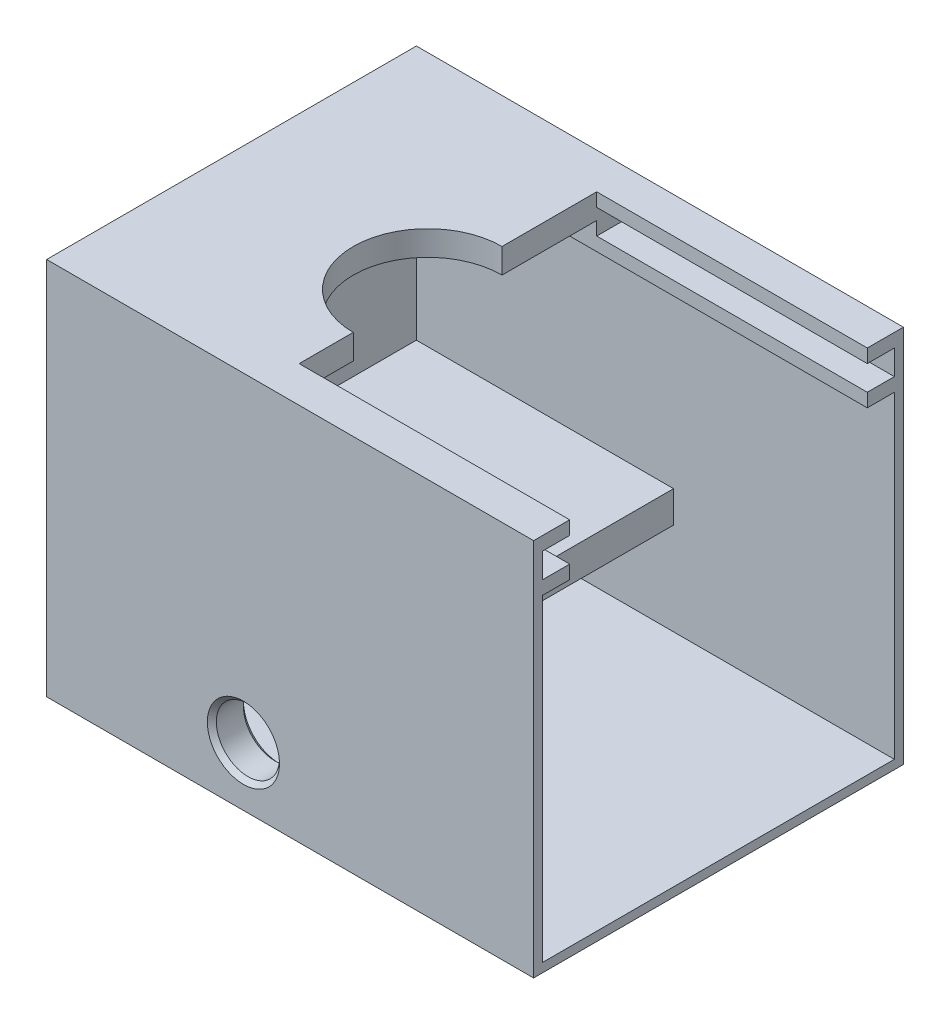
SolidWorks part; units mm, degrees
ref_plane "Front Plane" through (0, 0, 0) normal (0, 0, 1) x (1, 0, 0)
ref_plane "Top Plane" through (0, 0, 0) normal (0, 1, 0) x (1, 0, 0)
ref_plane "Right Plane" through (0, 0, 0) normal (1, 0, 0) x (0, 0, -1)
sketch "Sketch2" plane through (0, 0, 0) normal (0, 1, 0) x (1, 0, 0)
  line L1 (84.1818, -57.3934) -> (-28.8182, -57.3934)
  line L2 (84.1818, -57.3934) -> (84.1818, 19.6066)
  line L3 (84.1818, 19.6066) -> (-28.8182, 19.6066)
  line L4 (-28.8182, -57.3934) -> (-28.8182, 19.6066)
  dimension "D1" = 113
  dimension "D2" = 77
extrude "Boss-Extrude1" add sketch "Sketch2" along normal blind 80
sketch "Sketch3" plane through (84.1818, 0, 0) normal (1, 0, 0) x (0, 0, -1)
  line L0 (-57.3934, 80) -> (-57.3934, 0) construction
  line L1 (-55.3934, 80) -> (17.6066, 80)
  line L2 (-55.3934, 80) -> (-55.3934, 2)
  line L3 (-55.3934, 2) -> (17.6066, 2)
  line L4 (17.6066, 80) -> (17.6066, 2)
  line L5 (19.6066, 80) -> (19.6066, 0) construction
  line L6 (-57.3934, 0) -> (19.6066, 0) construction
  line L7 (-57.3934, 80) -> (19.6066, 80) construction
  dimension "D1" = 2
  dimension "D2" = 2
  dimension "D3" = 2
  dimension "D4" = 0
extrude "Cut-Extrude1" cut sketch "Sketch3" against normal blind 111
sketch "Sketch4" plane through (0, 0, 57.3934) normal (0, 0, 1) x (1, 0, 0)
  line L0 (-28.8182, 0) -> (84.1818, 0) construction
  line L1 (-28.8182, 80) -> (-28.8182, 0) construction
  circle A0 centre (19.8218, 13) radius 7
  dimension "D1" = 14
  dimension "D2" = 13
  dimension "D3" = 48.64
extrude "Cut-Extrude2" cut sketch "Sketch4" against normal blind 43
chamfer "Chamfer1" distance 1 angle 45 1 edges at (26.8218, 13, 57.3934)
sketch "Sketch5" plane through (0, 0, 55.3934) normal (0, 0, -1) x (-1, 0, 0)
  circle A0 centre (-19.8218, 13) radius 9
  dimension "D1" = 18
extrude "Boss-Extrude2" add sketch "Sketch5" along normal blind 6
hole_wizard "CSK for M12 SFHCS1" positions "Sketch6" profile "Sketch7" countersink size "M12" standard "ANSI Metric"
sketch "Sketch6" plane through (0, 0, 49.3934) normal (0, 0, -1) x (-1, 0, 0)
  point P0 (-19.8218, 13)
sketch "Sketch7" plane through (19.8218, 13, 49.3934) normal (1, 0, 0) x (0, 1, 0)
  line L0 (0, 0) -> (0, 12.206)
  line L1 (0, 12.206) -> (7, 8)
  line L2 (7, 8) -> (7, 1)
  line L3 (7, 1) -> (8, 0)
  line L5 (8, 0) -> (0, 0)
  line L6 (-7, 1) -> (-8, 0) construction
  line L10 (0, 12.206) -> (-7, 8) construction
  line L11 (0, -6.35) -> (0, 107.95) construction
  dimension "Hole Dia." = 14
  dimension "Hole Depth" = 8
  dimension "Near C'Sink Dia." = 16
  dimension "Near C'Sink Angle" = 90
  dimension "Drill Angle" = 118
ref_plane "Plane3" through (25.2118, 0, 0) normal (1, 0, 0) x (0, 0, -1)
sketch "Sketch8" plane through (25.2118, 0, 0) normal (1, 0, 0) x (0, 0, -1)
  line L0 (-35.8934, 29.5) -> (-5.8934, 29.5)
  line L1 (-31.4934, 25.1) -> (-33.4934, 25.1)
  line L4 (-35.8934, 22.5) -> (-31.4934, 22.5)
  line L5 (-31.4934, 22.5) -> (-31.4934, 25.1)
  line L6 (-33.4934, 25.1) -> (-33.4934, 27.1)
  line L7 (-5.8934, 22.5) -> (-10.2934, 22.5)
  line L8 (-10.2934, 22.5) -> (-10.2934, 25.1)
  line L9 (-10.2934, 25.1) -> (-8.2934, 25.1)
  line L10 (-8.2934, 25.1) -> (-8.2934, 27.1)
  line L11 (-33.4934, 27.1) -> (-8.2934, 27.1)
  line L12 (-55.3934, 80) -> (-55.3934, 2) construction
  line L13 (-35.8934, 22.5) -> (-55.3934, 22.5)
  line L14 (-55.3934, 2) -> (17.6066, 2) construction
  line L15 (-55.3934, 22.5) -> (-55.3934, 29.5)
  line L16 (-55.3934, 29.5) -> (-35.8934, 29.5)
  line L17 (17.6066, 2) -> (17.6066, 80) construction
  line L18 (-5.8934, 29.5) -> (17.6066, 29.5)
  line L20 (-5.8934, 22.5) -> (17.6066, 22.5)
  line L21 (17.6066, 29.5) -> (17.6066, 22.5)
  dimension "D1" = 30
  dimension "D2" = 7
  dimension "D3" = 7
  dimension "D4" = 4.4
  dimension "D5" = 2.6
  dimension "D6" = 2
  dimension "D7" = 2
  dimension "D8" = 4.4
  dimension "D9" = 2.6
  dimension "D10" = 2
  dimension "D11" = 2
  dimension "D13" = 20.5
sketch "Sketch9" plane through (-28.8182, 0, 0) normal (-1, 0, 0) x (0, 0, 1)
  line L1 (-19.6066, 80) -> (-19.6066, 0) construction
  line L2 (55.3934, 2) -> (-17.6066, 2) construction
  circle A0 centre (18.8934, 52) radius 2.5
  dimension "D1" = 5
  dimension "D2" = 50
  dimension "D3" = 38.5
extrude "Boss-Extrude3" add sketch "Sketch8" against normal blind 51.03 and the other way blind 10
sketch "Sketch11" plane through (0, 29.5, 0) normal (0, 1, 0) x (1, 0, 0)
  line L3 (35.2118, -30.8934) -> (25.2118, -30.8934)
  line L4 (35.2118, 17.6066) -> (35.2118, -55.3934) construction
  line L5 (35.2118, -55.3934) -> (-25.8182, -55.3934) construction
  line L6 (35.2118, -10.8934) -> (25.2118, -10.8934)
  arc A1 (25.2118, -30.8934) -> (25.2118, -10.8934) centre (25.2118, -20.8934) cw
  dimension "D1" = 10
  dimension "D2" = 24.5
  dimension "D3" = 10
  dimension "D4" = 20
extrude "Cut-Extrude4" cut sketch "Sketch9" against normal blind 18.03
sketch "Sketch15" plane through (-28.8182, 0, 0) normal (-1, 0, 0) x (0, 0, 1)
  line L0 (18.8902, 55.5) -> (16.9398, 65.3579)
  line L1 (16.8347, 54.8305) -> (7.7071, 59.5576)
  arc A0 (18.8902, 55.5) -> (16.8347, 54.8305) centre (18.8934, 52) ccw
  arc A1 (16.9398, 65.3579) -> (7.7071, 59.5576) centre (18.8934, 52) ccw
  dimension "D1" = 7
  dimension "D2" = 27
  dimension "D3" = 51.429
  dimension "D4" = 10.049
  dimension "D5" = 10.279
extrude "Cut-Extrude5" cut sketch "Sketch15" along normal blind 23.03 and the other way blind 30
ref_plane "Plane4" through (0, 52, 0) normal (0, 1, 0) x (1, 0, 0)
sketch "Sketch18" plane through (0, 52, 0) normal (0, 1, 0) x (1, 0, 0)
  line L1 (-26.8182, -18.8934) -> (-12.543, -18.8934)
pattern_circular "CirPattern1" count 6 over 360 about axis through (0, 52, 18.8934) along (1, 0, 0) of "Cut-Extrude5"
sketch "Sketch23" plane through (0, 80, 0) normal (0, 1, 0) x (1, 0, 0)
  line L1 (84.1818, -57.3934) -> (-28.8182, -57.3934)
  line L2 (84.1818, -57.3934) -> (84.1818, 19.6066)
  line L3 (84.1818, 19.6066) -> (-28.8182, 19.6066)
  line L4 (-28.8182, -57.3934) -> (-28.8182, 19.6066)
extrude "Boss-Extrude5" add sketch "Sketch23" along normal blind 4 and the other way blind 7.5
sketch "Sketch24" plane through (0, 84, 0) normal (0, 1, 0) x (1, 0, 0)
  line L0 (84.1818, -57.3934) -> (84.1818, 19.6066) construction
  line L2 (84.1818, -37.3934) -> (84.1818, -4.3934)
  line L4 (24.1818, -37.3934) -> (24.1818, -4.3934)
  arc A0 (24.1818, -37.3934) -> (24.1818, -4.3934) centre (24.1818, -20.8934) cw
  dimension "D2" = 60
  dimension "D3" = 33
extrude "Cut-Extrude6" cut sketch "Sketch24" against normal blind 10 contours A0 L4
sketch "Sketch27" plane through (0, 84, 0) normal (0, 1, 0) x (1, 0, 0)
  line L0 (84.1818, -57.3934) -> (84.1818, 19.6066) construction
  line L1 (84.1818, -49.3934) -> (24.1818, -49.3934)
  line L2 (84.1818, -49.3934) -> (84.1818, 16.6066)
  line L3 (84.1818, 16.6066) -> (24.1818, 16.6066)
  line L4 (24.1818, -49.3934) -> (24.1818, 16.6066)
  line L5 (-28.8182, -57.3934) -> (84.1818, -57.3934) construction
  line L6 (84.1818, 19.6066) -> (-28.8182, 19.6066) construction
  dimension "D1" = 60
  dimension "D2" = 8
  dimension "D3" = 3
extrude "Cut-Extrude7" cut sketch "Sketch27" against normal blind 14
sketch "Sketch28" plane through (84.1818, 0, 0) normal (1, 0, 0) x (0, 0, -1)
  line L0 (-49.3934, 72.5) -> (-49.3934, 84) construction
  line L1 (-49.3934, 80.8) -> (-51.1934, 80.8)
  line L2 (-49.3934, 80.8) -> (-49.3934, 83)
  line L3 (-49.3934, 83) -> (-51.1934, 83)
  line L4 (-51.1934, 80.8) -> (-51.1934, 83)
  line L5 (-57.3934, 84) -> (-49.3934, 84) construction
  line L7 (16.6066, 84) -> (16.6066, 72.5) construction
  line L8 (16.6066, 83) -> (18.4066, 83)
  line L9 (16.6066, 83) -> (16.6066, 80.8)
  line L10 (16.6066, 80.8) -> (18.4066, 80.8)
  line L11 (18.4066, 83) -> (18.4066, 80.8)
  line L12 (16.6066, 84) -> (19.6066, 84) construction
  dimension "D1" = 1.8
  dimension "D2" = 2.2
  dimension "D3" = 1
  dimension "D4" = 1.8
  dimension "D5" = 2.2
  dimension "D6" = 1
extrude "Cut-Extrude9" cut sketch "Sketch11" against normal blind 10 and the other way through all
sketch "Sketch29" plane through (24.1818, 0, 0) normal (1, 0, 0) x (0, 0, -1)
  line L0 (16.6066, 72.5) -> (16.6066, 84) construction
  line L1 (-49.3934, 72.5) -> (16.6066, 72.5)
  line L2 (-49.3934, 72.5) -> (-49.3934, 78.5)
  line L3 (-49.3934, 78.5) -> (16.6066, 78.5)
  line L4 (16.6066, 72.5) -> (16.6066, 78.5)
  dimension "D1" = 6
extrude "Cut-Extrude10" cut sketch "Sketch29" against normal blind 51
sketch "Sketch30" plane through (84.1818, 0, 0) normal (1, 0, 0) x (0, 0, -1)
  line L7 (-49.3934, 81) -> (-49.3934, 75.5)
  line L8 (-49.3934, 72.5) -> (-49.3934, 84) construction
  line L9 (-49.3934, 75.5) -> (-55.3934, 75.5)
  line L10 (-55.3934, 75.5) -> (-55.3934, 81)
  line L11 (-55.3934, 81) -> (-49.3934, 81)
  line L12 (-57.3934, 84) -> (-49.3934, 84) construction
  dimension "D1" = 5.5
  dimension "D2" = 6
  dimension "D3" = 3
extrude "Cut-Extrude11" cut sketch "Sketch30" against normal blind 60
sketch "Sketch36" plane through (0, 0, -19.6066) normal (0, 0, -1) x (-1, 0, 0)
  line L1 (-84.1818, 0) -> (28.8182, 0)
  line L2 (-84.1818, 0) -> (-84.1818, 84)
  line L3 (-84.1818, 84) -> (28.8182, 84)
  line L4 (28.8182, 0) -> (28.8182, 84)
extrude "Boss-Extrude9" add sketch "Sketch36" along normal blind 5
sketch "Sketch40" plane through (-26.8182, 0, 0) normal (1, 0, 0) x (0, 0, -1)
  line L1 (-8.1947, 27.1367) -> (-33.6268, 27.1367)
  line L2 (-8.1947, 27.1367) -> (-8.1947, 25.088)
  line L3 (-8.1947, 25.088) -> (-33.6268, 25.088)
  line L4 (-33.6268, 27.1367) -> (-33.6268, 25.088)
extrude "Boss-Extrude10" add sketch "Sketch40" along normal blind 35.8
sketch "Sketch42" plane through (84.1818, 0, 0) normal (1, 0, 0) x (0, 0, -1)
  line L0 (16.6066, 84) -> (16.6066, 72.5) construction
  line L1 (16.6066, 81) -> (22.6066, 81)
  line L2 (16.6066, 81) -> (16.6066, 75.5)
  line L3 (16.6066, 75.5) -> (22.6066, 75.5)
  line L4 (22.6066, 81) -> (22.6066, 75.5)
  line L5 (16.6066, 84) -> (24.6066, 84) construction
  dimension "D1" = 5.5
  dimension "D2" = 3
  dimension "D3" = 6
extrude "Cut-Extrude13" cut sketch "Sketch42" against normal blind 60
sketch "Sketch46" plane through (0, 29.5, 0) normal (0, 1, 0) x (1, 0, 0)
  line L0 (35.2118, -55.3934) -> (-25.8182, -55.3934) construction
  line L1 (-25.8182, 17.6066) -> (-26.8182, 17.6066)
  line L2 (-25.8182, 17.6066) -> (-25.8182, -55.3934)
  line L3 (-25.8182, -55.3934) -> (-26.8182, -55.3934)
  line L4 (-26.8182, 17.6066) -> (-26.8182, -55.3934)
extrude "Boss-Extrude11" add sketch "Sketch46" against normal up to surface (7 mm away) up to face at (4.6968, 22.5, 43.4434)
sketch "Sketch47" plane through (0, 0, -17.6066) normal (0, 0, 1) x (1, 0, 0)
  line L0 (-26.8182, 22.5) -> (-26.8182, 2)
  line L1 (-26.8182, 72.5) -> (84.1818, 72.5)
  line L2 (-26.8182, 72.5) -> (-26.8182, 29.5)
  line L3 (-26.8182, 2) -> (84.1818, 2)
  line L4 (84.1818, 72.5) -> (84.1818, 2)
  line L5 (35.2118, 22.5) -> (-26.8182, 22.5)
  line L6 (35.2118, 22.5) -> (35.2118, 29.5)
  line L7 (35.2118, 29.5) -> (-26.8182, 29.5)
extrude "Cut-Extrude14" cut sketch "Sketch47" against normal blind 5
sketch "Sketch48" plane through (0, 0, 55.3934) normal (0, 0, -1) x (-1, 0, 0)
  line L0 (26.8182, 2) -> (-84.1818, 2) construction
  line L1 (-35.2118, 22.5) -> (26.8182, 22.5) construction
  line L2 (5.6327, 2) -> (-28.8218, 2)
  line L3 (-28.8218, 22.5) -> (5.6327, 22.5)
  line L4 (-10.8218, 13) -> (5.6327, 2)
  line L5 (-10.8218, 13) -> (5.6327, 22.5)
  line L6 (-28.8218, 2) -> (-28.8218, 22.5)
  circle A0 centre (-19.8218, 13) radius 9 construction
  circle A1 centre (-19.8218, 13) radius 9
  circle M6 centre (-19.8218, 13) radius 9
  line M11 (-84.1818, 2) -> (26.8182, 2)
  line M13 (26.8182, 22.5) -> (-35.2118, 22.5)
  dimension "D1" = 30
extrude "Boss-Extrude12" add sketch "Sketch48" along normal up to surface (6 mm away) contours L6 L4 M11 M6 | L6 L5 M6 M13 up to face at (19.8218, 21, 49.3934)
ref_plane "Plane5" through (-23.8182, 0, 0) normal (-1, 0, 0) x (0, 0, 1)
sketch "Sketch49" plane through (-23.8182, 0, 0) normal (-1, 0, 0) x (0, 0, 1)
  line L0 (22.374, 52.3677) -> (31.0316, 57.9088) construction
  line L1 (31.4385, 47.0129) -> (21.9261, 50.2527) construction
  line L2 (20.9521, 49.1695) -> (30.0797, 44.4424) construction
  line L3 (20.847, 38.6421) -> (18.8966, 48.5) construction
  line L4 (57.3934, 84) -> (-24.6066, 84)
  line L5 (-24.6066, 84) -> (-24.6066, 0)
  line L6 (-24.6066, 0) -> (57.3934, 0)
  line L7 (57.3934, 0) -> (57.3934, 84)
  line L8 (57.3934, 84) -> (-24.6066, 84)
  line L9 (-24.6066, 84) -> (-24.6066, 0)
  line L10 (-24.6066, 0) -> (57.3934, 0)
  line L11 (57.3934, 0) -> (57.3934, 84)
  line L12 (17.4715, 48.8019) -> (17.9415, 38.5336) construction
  line L13 (8.3019, 43.6292) -> (15.8639, 50.2473) construction
  line L14 (15.4128, 51.6323) -> (6.7552, 46.0912) construction
  line L15 (6.3483, 56.9871) -> (15.8607, 53.7473) construction
  line L16 (16.8347, 54.8305) -> (7.7071, 59.5576) construction
  line L17 (16.9398, 65.3579) -> (18.8902, 55.5) construction
  line L18 (20.3153, 55.1981) -> (19.8453, 65.4664) construction
  line L19 (29.4849, 60.3708) -> (21.9229, 53.7527) construction
  line L20 (22.374, 52.3677) -> (31.0316, 57.9088)
  line L21 (31.4385, 47.0129) -> (21.9261, 50.2527)
  line L22 (20.9521, 49.1695) -> (30.0797, 44.4424)
  line L23 (20.847, 38.6421) -> (18.8966, 48.5)
  line L24 (17.4715, 48.8019) -> (17.9415, 38.5336)
  line L25 (8.3019, 43.6292) -> (15.8639, 50.2473)
  line L26 (15.4128, 51.6323) -> (6.7552, 46.0912)
  line L27 (6.3483, 56.9871) -> (15.8607, 53.7473)
  line L28 (16.8347, 54.8305) -> (7.7071, 59.5576)
  line L29 (16.9398, 65.3579) -> (18.8902, 55.5)
  line L30 (20.3153, 55.1981) -> (19.8453, 65.4664)
  line L31 (29.4849, 60.3708) -> (21.9229, 53.7527)
  line L32 (55.3934, 22.5) -> (-22.6066, 22.5) construction
  line L33 (-22.6066, 29.5) -> (55.3934, 29.5) construction
  line L34 (55.3934, 22.5) -> (-22.6066, 22.5)
  line L35 (-22.6066, 29.5) -> (55.3934, 29.5)
  arc A0 (31.4385, 47.0129) -> (31.0316, 57.9088) centre (18.8934, 52) ccw construction
  arc A1 (21.9261, 50.2527) -> (22.374, 52.3677) centre (18.8934, 52) ccw construction
  circle A2 centre (18.8934, 52) radius 2.5 construction
  arc A3 (18.8966, 48.5) -> (20.9521, 49.1695) centre (18.8934, 52) ccw construction
  arc A4 (20.847, 38.6421) -> (30.0797, 44.4424) centre (18.8934, 52) ccw construction
  arc A5 (8.3019, 43.6292) -> (17.9415, 38.5336) centre (18.8934, 52) ccw construction
  arc A6 (15.8639, 50.2473) -> (17.4715, 48.8019) centre (18.8934, 52) ccw construction
  arc A7 (15.8607, 53.7473) -> (15.4128, 51.6323) centre (18.8934, 52) ccw construction
  arc A8 (6.3483, 56.9871) -> (6.7552, 46.0912) centre (18.8934, 52) ccw construction
  arc A9 (16.9398, 65.3579) -> (7.7071, 59.5576) centre (18.8934, 52) ccw construction
  arc A10 (18.8902, 55.5) -> (16.8347, 54.8305) centre (18.8934, 52) ccw construction
  arc A11 (21.9229, 53.7527) -> (20.3153, 55.1981) centre (18.8934, 52) ccw construction
  arc A12 (29.4849, 60.3708) -> (19.8453, 65.4664) centre (18.8934, 52) ccw construction
  arc A13 (31.4385, 47.0129) -> (31.0316, 57.9088) centre (18.8934, 52) ccw
  arc A14 (21.9261, 50.2527) -> (22.374, 52.3677) centre (18.8934, 52) ccw
  circle A15 centre (18.8934, 52) radius 2.5
  arc A16 (18.8966, 48.5) -> (20.9521, 49.1695) centre (18.8934, 52) ccw
  arc A17 (20.847, 38.6421) -> (30.0797, 44.4424) centre (18.8934, 52) ccw
  arc A18 (8.3019, 43.6292) -> (17.9415, 38.5336) centre (18.8934, 52) ccw
  arc A19 (15.8639, 50.2473) -> (17.4715, 48.8019) centre (18.8934, 52) ccw
  arc A20 (15.8607, 53.7473) -> (15.4128, 51.6323) centre (18.8934, 52) ccw
  arc A21 (6.3483, 56.9871) -> (6.7552, 46.0912) centre (18.8934, 52) ccw
  arc A22 (16.9398, 65.3579) -> (7.7071, 59.5576) centre (18.8934, 52) ccw
  arc A23 (18.8902, 55.5) -> (16.8347, 54.8305) centre (18.8934, 52) ccw
  arc A24 (21.9229, 53.7527) -> (20.3153, 55.1981) centre (18.8934, 52) ccw
  arc A25 (29.4849, 60.3708) -> (19.8453, 65.4664) centre (18.8934, 52) ccw
  dimension "D1" = 0
extrude "Boss-Extrude13" add sketch "Sketch49" against normal blind 2
sketch "Sketch50" plane through (-28.8182, 0, 0) normal (-1, 0, 0) x (0, 0, 1)
  line L1 (57.3934, 0) -> (-24.6066, 0)
  line L2 (57.3934, 0) -> (57.3934, 84)
  line L3 (57.3934, 84) -> (-24.6066, 84)
  line L4 (-24.6066, 0) -> (-24.6066, 84)
extrude "Cut-Extrude15" cut sketch "Sketch50" against normal up to surface (5 mm away) up to face at (-23.8182, 59.0956, 14.9268)
